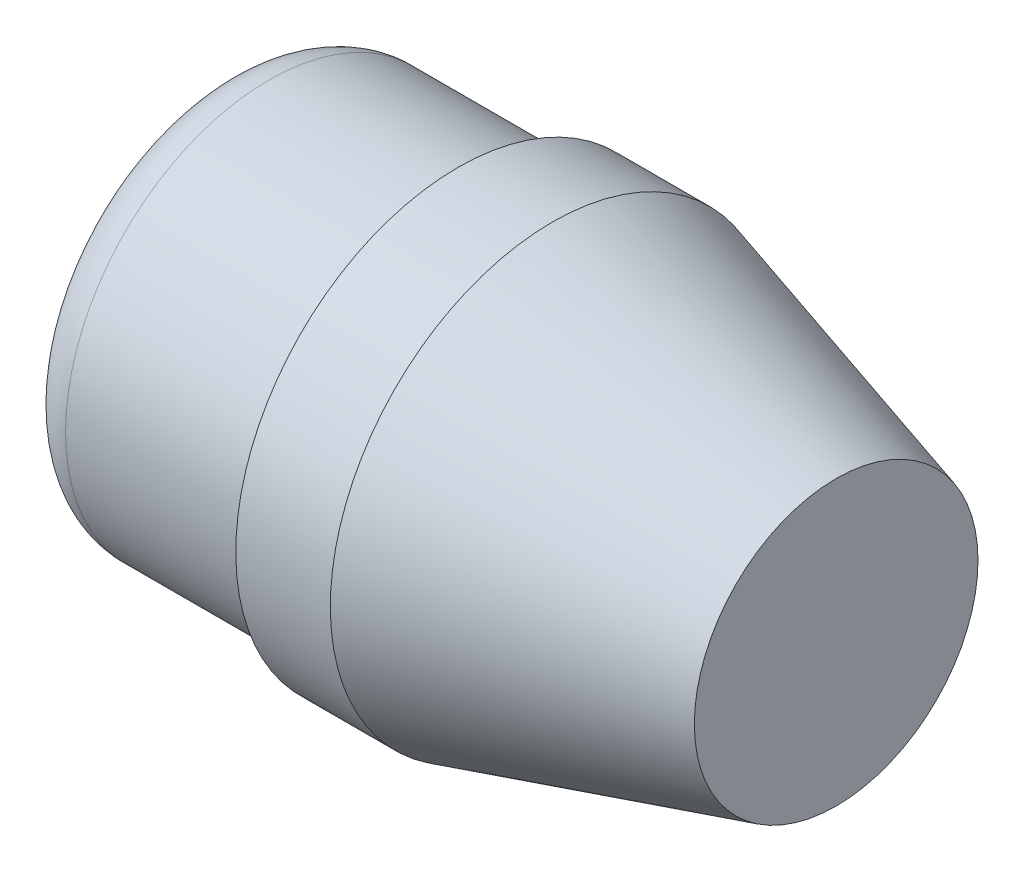
SolidWorks part; units mm, degrees
ref_plane "Plano frontal" through (0, 0, 0) normal (0, 0, 1) x (1, 0, 0)
ref_plane "Plano superior" through (0, 0, 0) normal (0, 1, 0) x (1, 0, 0)
ref_plane "Plano direito" through (0, 0, 0) normal (1, 0, 0) x (0, 0, -1)
sketch "Esboço1" plane through (0, 0, 0) normal (0, 0, 1) x (1, 0, 0)
  line L0 (0, 0) -> (0, 4.3)
  line L1 (0, 4.3) -> (5, 4.3)
  line L2 (5, 4.3) -> (5, 4.7)
  line L3 (5, 4.7) -> (7, 4.7)
  line L4 (7, 4.7) -> (13, 3)
  line L5 (13, 3) -> (13, 0)
  line L6 (13, 0) -> (0, 0)
  point P3 (6.5, 0)
  dimension "D1" = 5
  dimension "D2" = 2
  dimension "D3" = 3
  dimension "D4" = 13
  dimension "D5" = 4.7
  dimension "D6" = 4.3
  dimension "D7" = 15.819
revolve "Revolução1" add sketch "Esboço1" angle 360 about L6
fillet "Filete1" radius 1 1 edges at (0, 4.3, 0)
